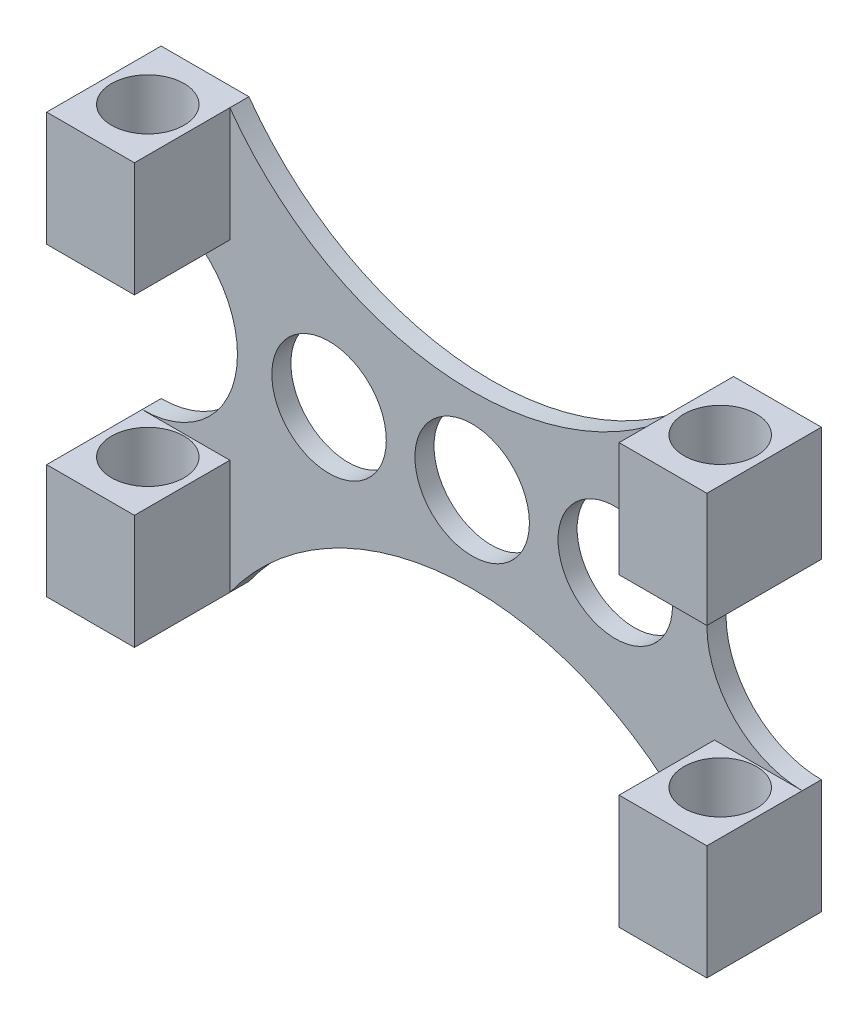
SolidWorks part; units mm, degrees
ref_plane "Front Plane" through (0, 0, 0) normal (0, 0, 1) x (1, 0, 0)
ref_plane "Top Plane" through (0, 0, 0) normal (0, 1, 0) x (1, 0, 0)
ref_plane "Right Plane" through (0, 0, 0) normal (1, 0, 0) x (0, 0, -1)
sketch "Sketch1" plane through (0, 0, 0) normal (0, 0, 1) x (1, 0, 0)
  line L0 (121.888, -49.8909) -> (-51.112, -49.8909) construction
  line L1 (-51.112, 5.1091) -> (-28.112, 5.1091)
  line L2 (-51.112, 5.1091) -> (-51.112, -24.8909)
  line L3 (-51.112, -104.8909) -> (-28.112, -104.8909)
  line L4 (121.888, 5.1091) -> (121.888, -24.8909)
  line L5 (-51.112, 5.1091) -> (-28.112, 5.1091) construction
  line L6 (-51.112, 5.1091) -> (-51.112, -24.8909) construction
  line L7 (-51.112, -24.8909) -> (-28.112, -24.8909) construction
  line L8 (-28.112, 5.1091) -> (-28.112, -24.8909) construction
  line L9 (-51.112, -104.8909) -> (-28.112, -104.8909) construction
  line L10 (-51.112, -104.8909) -> (-51.112, -74.8909) construction
  line L11 (-51.112, -74.8909) -> (-28.112, -74.8909) construction
  line L12 (-28.112, -104.8909) -> (-28.112, -74.8909) construction
  line L13 (121.888, -104.8909) -> (98.888, -104.8909) construction
  line L14 (121.888, -104.8909) -> (121.888, -74.8909) construction
  line L15 (121.888, -74.8909) -> (98.888, -74.8909) construction
  line L16 (98.888, -104.8909) -> (98.888, -74.8909) construction
  line L17 (121.888, 5.1091) -> (98.888, 5.1091) construction
  line L18 (121.888, 5.1091) -> (121.888, -24.8909) construction
  line L19 (121.888, -24.8909) -> (98.888, -24.8909) construction
  line L20 (98.888, 5.1091) -> (98.888, -24.8909) construction
  line L21 (35.388, 45.1091) -> (35.388, -104.8909) construction
  line L22 (98.888, 5.1091) -> (121.888, 5.1091)
  line L23 (121.888, -74.8909) -> (121.888, -104.8909)
  line L24 (98.888, -104.8909) -> (121.888, -104.8909)
  line L25 (-51.112, -74.8909) -> (-51.112, -104.8909)
  circle A0 centre (35.388, -49.8909) radius 15
  arc A1 (-51.112, -74.8909) -> (-51.112, -24.8909) centre (-51.112, -49.8909) ccw
  arc A2 (-28.112, -104.8909) -> (98.888, -104.8909) centre (35.388, -150.4046) cw
  arc A3 (121.888, -74.8909) -> (121.888, -24.8909) centre (121.888, -49.8909) cw
  arc A4 (-28.112, 5.1091) -> (98.888, 5.1091) centre (35.388, 50.6227) ccw
  circle A5 centre (72.888, -49.8909) radius 15
  circle A6 centre (-2.112, -49.8909) radius 15
  dimension "D5" = 30
  dimension "D6" = 37.5
  dimension "D7" = 37.5
  dimension "D1" = 150
  dimension "D2" = 110
  dimension "D3" = 23
  dimension "D4" = 30
extrude "Boss-Extrude1" add sketch "Sketch1" along normal blind 5
sketch "Sketch2" plane through (0, 0, 5) normal (0, 0, 1) x (1, 0, 0)
  line L1 (-51.112, 5.1091) -> (-28.112, 5.1091)
  line L2 (-51.112, 5.1091) -> (-51.112, -24.8909)
  line L3 (-51.112, -24.8909) -> (-28.112, -24.8909)
  line L4 (-28.112, 5.1091) -> (-28.112, -24.8909)
  line L5 (121.888, 5.1091) -> (98.8865, 5.1091)
  line L6 (121.888, 5.1091) -> (121.888, -24.8909)
  line L7 (121.888, -24.8909) -> (98.8865, -24.8909)
  line L8 (98.8865, 5.1091) -> (98.8865, -24.8909)
  line L9 (121.888, -104.8909) -> (98.8865, -104.8909)
  line L10 (121.888, -104.8909) -> (121.888, -74.8909)
  line L11 (121.888, -74.8909) -> (98.8865, -74.8909)
  line L12 (98.8865, -104.8909) -> (98.8865, -74.8909)
  line L13 (-51.112, -104.8909) -> (-28.112, -104.8909)
  line L14 (-51.112, -104.8909) -> (-51.112, -74.8909)
  line L15 (-51.112, -74.8909) -> (-28.112, -74.8909)
  line L16 (-28.112, -104.8909) -> (-28.112, -74.8909)
  dimension "D1" = 23
  dimension "D2" = 30
extrude "Boss-Extrude2" add sketch "Sketch2" along normal blind 25
sketch "Sketch3" plane through (0, -104.8909, 0) normal (0, -1, 0) x (1, 0, 0)
  line L0 (-39.612, 30) -> (-39.612, 0) construction
  line L1 (-51.112, 30) -> (-28.112, 30) construction
  line L2 (-51.112, 0) -> (-28.112, 0) construction
  line L3 (110.3873, 30) -> (110.388, 0) construction
  line L4 (98.8865, 30) -> (121.888, 30) construction
  line L5 (98.888, 0) -> (121.888, 0) construction
  circle A0 centre (110.3876, 15) radius 9.5
  circle A1 centre (-39.612, 15) radius 9.5
  dimension "D1" = 19
  dimension "D2" = 15
extrude "Cut-Extrude1" cut sketch "Sketch3" against normal up to surface (110 mm away) up to face at (-37.312, 5.1091, 13)
ref_plane "Plane1" through (0, -49.8909, 0) normal (0, 1, 0) x (1, 0, 0)
